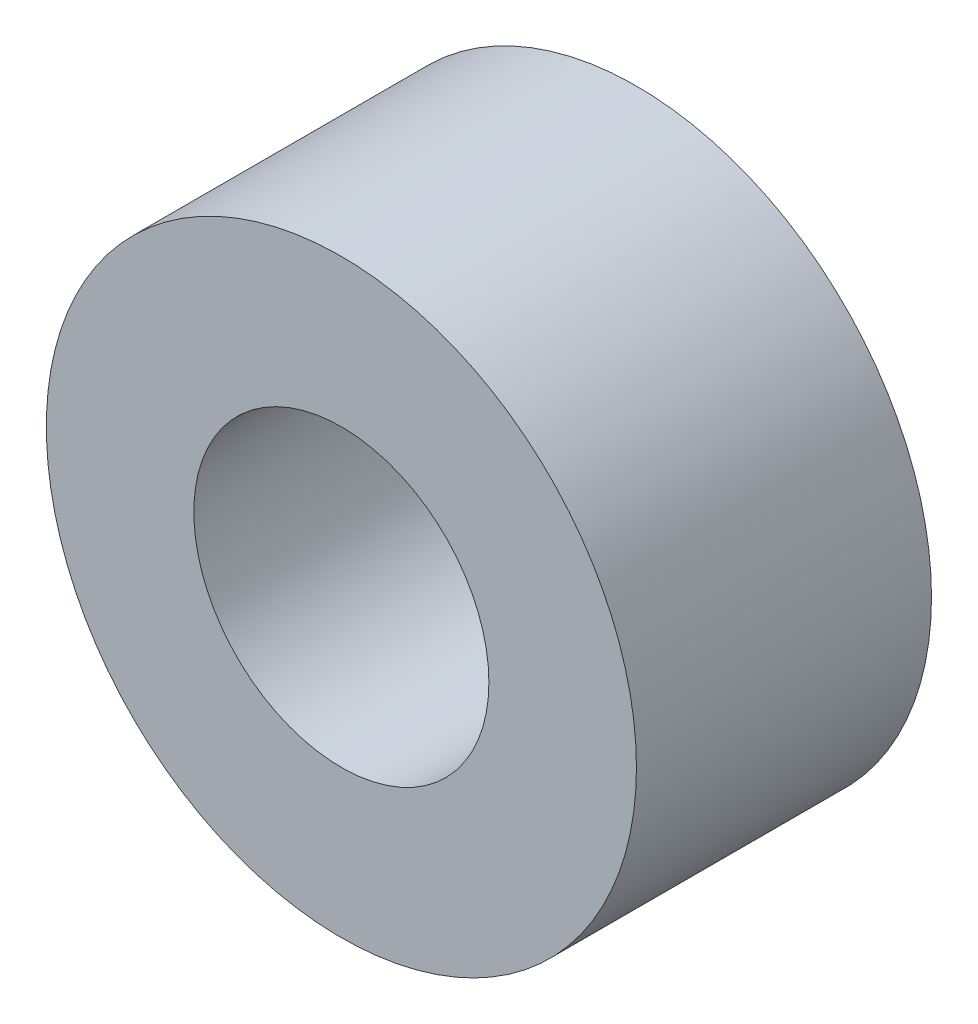
SolidWorks part; units mm, degrees
material "Brass"
ref_plane "Front Plane" through (0, 0, 0) normal (0, 0, 1) x (1, 0, 0)
ref_plane "Top Plane" through (0, 0, 0) normal (0, 1, 0) x (1, 0, 0)
ref_plane "Right Plane" through (0, 0, 0) normal (1, 0, 0) x (0, 0, -1)
sketch "Sketch1" plane through (0, 0, 0) normal (0, 0, 1) x (1, 0, 0)
  circle A0 centre (0, 0) radius 3.175
  circle A1 centre (0, 0) radius 3.175
  circle A4 centre (0, 0) radius 1.5875
  dimension "D1" = 6.35
  dimension "D2" = 3.175
extrude "Boss-Extrude1" add sketch "Sketch1" along normal blind 3.175 contours A0 A4
